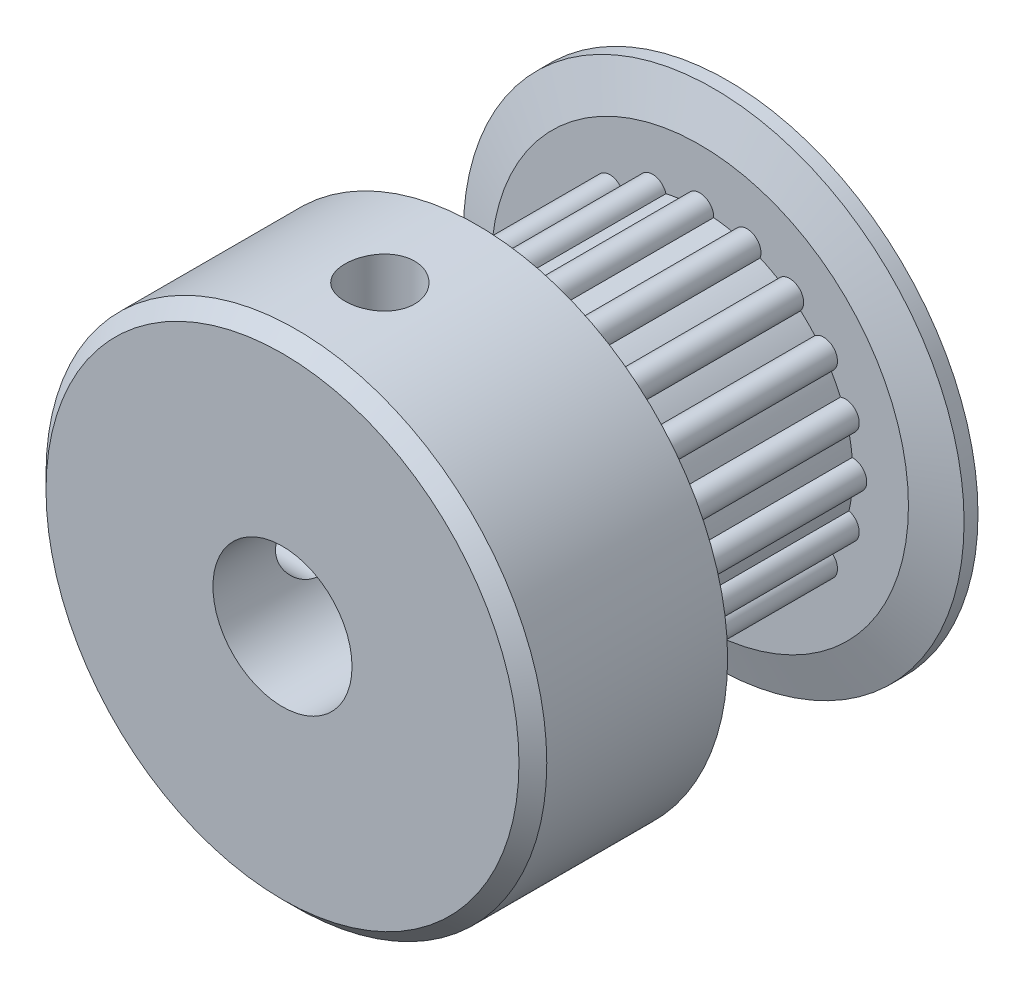
SolidWorks part; units mm, degrees
ref_plane "Front" through (0, 0, 0) normal (0, 0, 1) x (1, 0, 0)
ref_plane "Top" through (0, 0, 0) normal (0, 1, 0) x (1, 0, 0)
ref_plane "Right" through (0, 0, 0) normal (1, 0, 0) x (0, 0, -1)
sketch "Sketch1" plane through (0, 0, 0) normal (1, 0, 0) x (0, 0, -1)
  line L0 (0, 0) -> (16.6784, 0) construction
  line L1 (50, 0) -> (-50, 0) construction
  line L2 (0, 0) -> (0, 25.6646) construction
  line L3 (-3.75, 7.5) -> (-3.75, 5.5)
  line L4 (-3.75, 5.5) -> (3.75, 5.5)
  line L5 (3.75, 5.5) -> (3.75, 7.5)
  line L6 (4.25, 9) -> (4.75, 9)
  line L7 (4.75, 9) -> (4.75, 2.5)
  line L8 (4.75, 2.5) -> (-11.25, 2.5)
  line L9 (-11.25, 2.5) -> (-11.25, 9)
  line L10 (-11.25, 9) -> (-4.25, 9)
  line L11 (-4.25, 9) -> (-3.75, 7.5)
  line L12 (4.25, 9) -> (3.75, 7.5)
  dimension "D1" = 18
  dimension "D2" = 5
  dimension "D3" = 7.5
  dimension "D4" = 7.5
  dimension "D5" = 16
  dimension "D6" = 11
  dimension "D7" = 1.5
  dimension "D8" = 0.5
revolve "Revolve1" add sketch "Sketch1" angle 360 about L0
ref_plane "Plane1" through (0, 0, 7.75) normal (0, 0, 1) x (1, 0, 0)
hole_wizard "M3x0.5 Tapped Hole1" positions "3DSketch1" profile "Sketch3" tap size "M3x0.5" standard "ANSI Metric"
sketch3d "3DSketch1"
  point P0 (-9, 0, 7.75)
  point P2 (0, 9, 7.75)
cosmetic thread "Hole Thread3" parameters "D2"=3
cosmetic thread "Hole Thread4" parameters "D2"=3
sketch "Sketch3" plane through (-9, 0, 7.75) normal (0, 1, 0) x (0, 0, 1)
  line L0 (0, 0) -> (0, 6.5)
  line L1 (0, 6.5) -> (1.25, 6.5)
  line L2 (1.25, 6.5) -> (1.25, 0)
  line L5 (1.25, 0) -> (0, 0)
  line L11 (0, -6.35) -> (0, 107.95) construction
  dimension "Thru Tap Drill Dia." = 2.5
  dimension "Thru Tap Drill Depth" = 6.5
chamfer "Chamfer1" distance 0.5 angle 45 1 edges at (9, 0, 11.25)
sketch "Sketch4" plane through (0, 0, 3.75) normal (0, 0, -1) x (-1, 0, 0)
  line L0 (0, 0) -> (0, 9.5953) construction
  circle A0 centre (0, 0) radius 5.5 construction
  circle A1 centre (0, 0) radius 2.5 construction
  circle A2 centre (0, 0) radius 5.5 construction
  arc A3 (-0.4995, 5.4773) -> (0.4995, 5.4773) centre (0, 5.5) cw
  arc A4 (-0.4995, 5.4773) -> (0.4995, 5.4773) centre (0, 0) cw
  dimension "D1" = 0.5
extrude "Boss-Extrude1" add sketch "Sketch4" along normal up to surface (7.5 mm away) up to face at (5.5, 0, -3.75)
pattern_circular "CirPattern1" count 20 over 360 about axis through (0, 0, 0) along (0, 0, 1) of "Boss-Extrude1"
